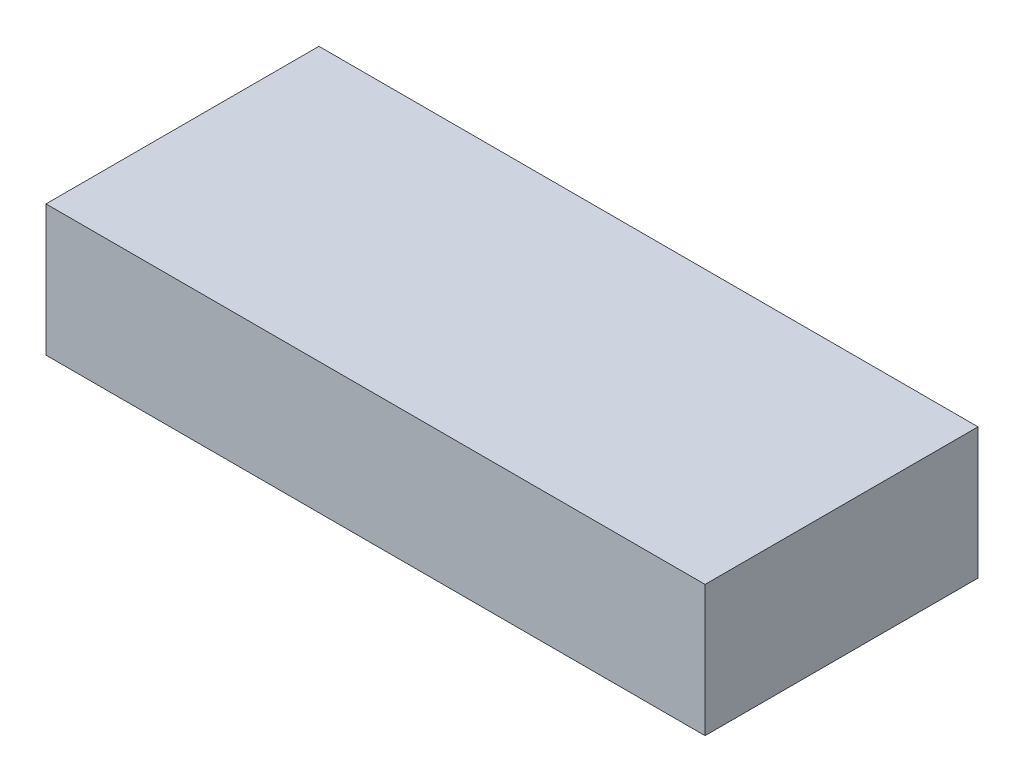
SolidWorks part; units mm, degrees
ref_plane "Front Plane" through (0, 0, 0) normal (0, 0, 1) x (1, 0, 0)
ref_plane "Top Plane" through (0, 0, 0) normal (0, 1, 0) x (1, 0, 0)
ref_plane "Right Plane" through (0, 0, 0) normal (1, 0, 0) x (0, 0, -1)
sketch "Sketch1" plane through (0, 0, 0) normal (0, 0, 1) x (1, 0, 0)
  line L1 (-25.15, -5) -> (25.15, -5)
  line L2 (-25.15, -5) -> (-25.15, 5)
  line L3 (-25.15, 5) -> (25.15, 5)
  line L4 (25.15, -5) -> (25.15, 5)
  line L5 (-25.15, -5) -> (25.15, 5) construction
  line L6 (-25.15, 5) -> (25.15, -5) construction
  point P0 (0, 0)
extrude "Envelope" add sketch "Sketch1" along normal blind 20.83
